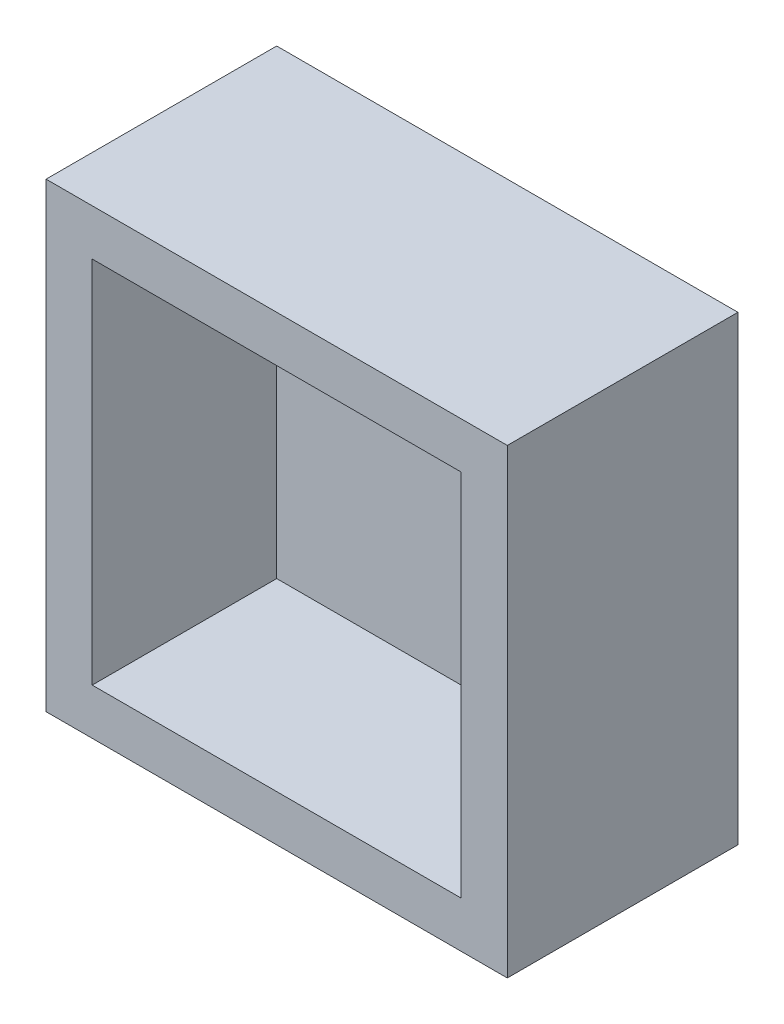
SolidWorks part; units mm, degrees
ref_plane "前视基准面" through (0, 0, 0) normal (0, 0, 1) x (1, 0, 0)
ref_plane "上视基准面" through (0, 0, 0) normal (0, 1, 0) x (1, 0, 0)
ref_plane "右视基准面" through (0, 0, 0) normal (1, 0, 0) x (0, 0, -1)
other "Configuration Table"
sketch "草图1" plane through (0, 0, 0) normal (0, 0, 1) x (1, 0, 0)
  line L1 (0, 0) -> (20, 0)
  line L2 (0, 0) -> (0, 20)
  line L3 (0, 20) -> (20, 20)
  line L4 (20, 0) -> (20, 20)
extrude "BaseBox" add sketch "草图1" along normal blind 10
shell "Shell" thickness 2
